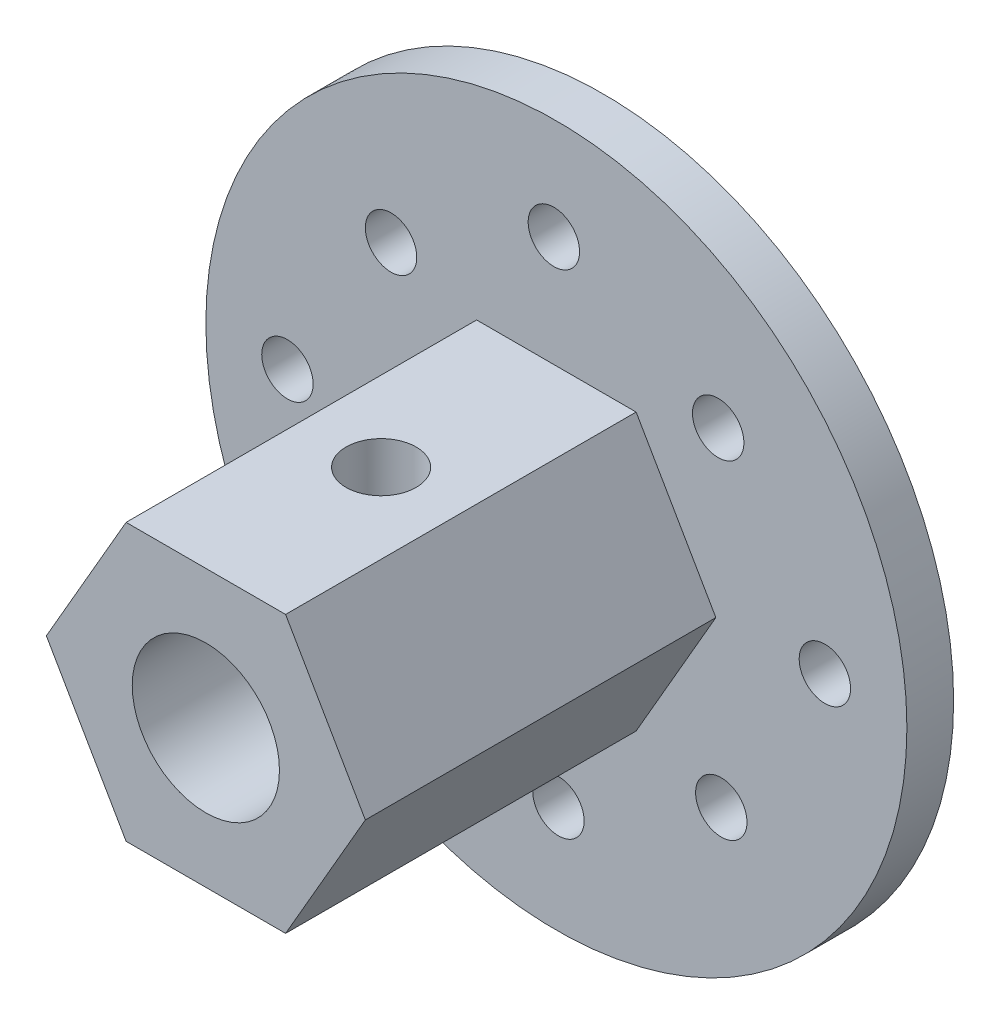
SolidWorks part; units mm, degrees
ref_plane "前视基准面" through (0, 0, 0) normal (0, 0, 1) x (1, 0, 0)
ref_plane "上视基准面" through (0, 0, 0) normal (0, 1, 0) x (1, 0, 0)
ref_plane "右视基准面" through (0, 0, 0) normal (1, 0, 0) x (0, 0, -1)
other "Configuration Table"
sketch "草图1" plane through (0, 0, 0) normal (0, 0, 1) x (1, 0, 0)
  line L1 (6.825, 0) -> (3.4125, 5.9106)
  line L2 (3.4125, 5.9106) -> (-3.4125, 5.9106)
  line L3 (-3.4125, 5.9106) -> (-6.825, 0)
  line L4 (-6.825, 0) -> (-3.4125, -5.9106)
  line L5 (-3.4125, -5.9106) -> (3.4125, -5.9106)
  line L6 (3.4125, -5.9106) -> (6.825, 0)
  circle A1 centre (0, 0) radius 6.825 construction
  circle A2 centre (0, 0) radius 3.15
  dimension "D1" = 6.3
extrude "凸台-拉伸1" add sketch "草图1" along normal blind 15 contours L5 L6 L1 L2 L3 L4 A2
sketch "草图2" plane through (0, 0, 0) normal (0, 0, -1) x (-1, 0, 0)
  circle A0 centre (0, 0) radius 15
  circle A1 centre (0, 0) radius 3.15
  circle A2 centre (0.1078, 10.6418) radius 1.1
  circle A3 centre (7.0747, 6.9494) radius 1.1
  circle A4 centre (11.5093, 0.0349) radius 1.1
  circle A5 centre (6.9424, -7.0504) radius 1.1
  circle A6 centre (-0.088, -10.3573) radius 1.1
  circle A7 centre (-7.0576, -6.9195) radius 1.1
  circle A8 centre (-11.4897, 0.2494) radius 1.1
  circle A9 centre (-6.9245, 7.0773) radius 1.1
  dimension "D1" = 2.2
  dimension "D2" = 2.2
  dimension "D3" = 2.2
  dimension "D4" = 2.2
  dimension "D5" = 2.2
  dimension "D6" = 2.2
  dimension "D7" = 2.2
  dimension "D8" = 2.2
  dimension "D9" = 6.3
extrude "凸台-拉伸2" add sketch "草图2" along normal blind 2
sketch "草图3" plane through (0, 5.9106, 0) normal (0, 1, 0) x (1, 0, 0)
  line L0 (3.4125, -7.5) -> (-3.4125, -7.5) construction
  line L1 (3.4125, -15) -> (3.4125, 0) construction
  line L2 (-3.4125, -15) -> (-3.4125, 0) construction
  circle A0 centre (0, -7.5) radius 1.5
extrude "切除-拉伸1" cut sketch "草图3" against normal through all
